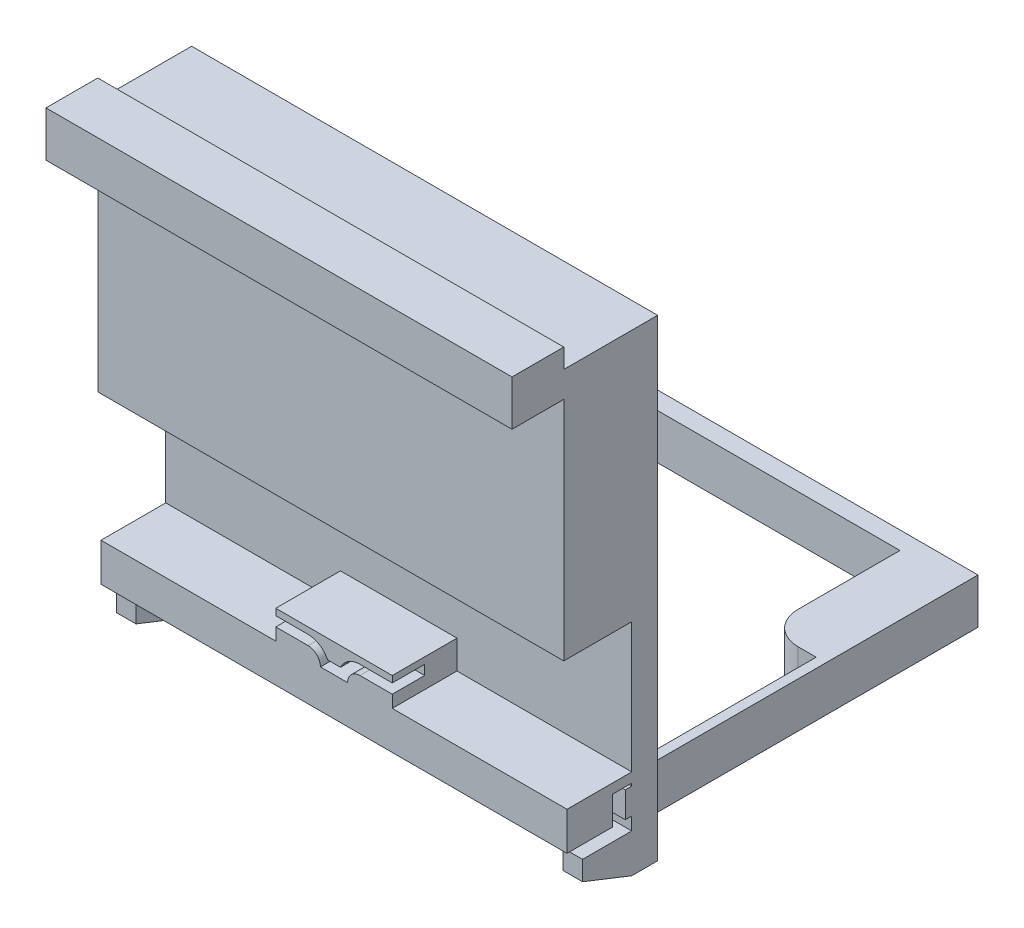
SolidWorks part; units mm, degrees
ref_plane "Alzado" through (0, 0, 0) normal (0, 0, 1) x (1, 0, 0)
ref_plane "Planta" through (0, 0, 0) normal (0, 1, 0) x (1, 0, 0)
ref_plane "Vista lateral" through (0, 0, 0) normal (1, 0, 0) x (0, 0, -1)
sketch "Croquis1" plane through (0, 0, 0) normal (0, 0, 1) x (1, 0, 0)
  line L1 (36, -39.5) -> (-36, -39.5)
  line L5 (36, -39.5) -> (-36, 39.5) construction
  line L6 (36, 39.5) -> (-36, -39.5) construction
  line L7 (-36, -39.5) -> (-33, -39.5)
  line L8 (-36, -39.5) -> (-36, -30.5)
  line L9 (-36, -30.5) -> (-33, -30.5)
  line L10 (-33, -39.5) -> (-33, -30.5)
  line L11 (-36, -30.5) -> (-26.5, -30.5)
  line L12 (-36, -30.5) -> (-36, -27)
  line L13 (-36, -27) -> (-26.5, -27)
  line L14 (-26.5, -30.5) -> (-26.5, -27)
  line L22 (21.8, 10.2) -> (36, 10.2) construction
  line L23 (-36, -27) -> (-36, -23.5) construction
  line L24 (36, -39.5) -> (33, -39.5)
  line L25 (36, -39.5) -> (36, -30.5)
  line L26 (36, -30.5) -> (33, -30.5)
  line L27 (33, -39.5) -> (33, -30.5)
  line L28 (36, -30.5) -> (26.5, -30.5)
  line L29 (36, -30.5) -> (36, -27)
  line L30 (36, -27) -> (26.5, -27)
  line L31 (26.5, -30.5) -> (26.5, -27)
  line L32 (-36, -39.5) -> (-33, -39.5)
  line L33 (-36, -39.5) -> (-36, -32.5)
  line L34 (-36, -32.5) -> (-33, -32.5)
  line L35 (-33, -39.5) -> (-33, -32.5)
  line L36 (36, -39.5) -> (33, -39.5)
  line L37 (36, -39.5) -> (36, -32.5)
  line L38 (36, -32.5) -> (33, -32.5)
  line L39 (33, -39.5) -> (33, -32.5)
  line L40 (36, -22) -> (36, -6) construction
  line L41 (-36, -23.5) -> (36, -23.5)
  line L42 (-36, -23.5) -> (-36, -22)
  line L43 (-36, -22) -> (36, -22)
  line L44 (36, -23.5) -> (36, -22)
  line L45 (-36, -22) -> (36, -22)
  line L49 (-36, -22) -> (-36, 10.2) construction
  line L50 (36, 10.2) -> (36, 17.2) construction
  line L52 (21.8, -6) -> (-21.8, -6)
  line L53 (21.8, -6) -> (21.8, 10.2)
  line L54 (21.8, 10.2) -> (-21.8, 10.2)
  line L55 (-21.8, -6) -> (-21.8, 10.2)
  line L56 (-17.5, 34.5) -> (-36, 34.5)
  line L61 (17.5, 34.5) -> (36, 34.5)
  line L63 (-36, 34.5) -> (36, 34.5)
  line L64 (-36, 34.5) -> (-36, -39.5)
  line L65 (-36, -39.5) -> (36, -39.5)
  line L66 (36, 34.5) -> (36, -39.5)
  line L69 (-17.5, 34.5) -> (17.5, 34.5)
  line L71 (36, 17.2) -> (-36, 17.2)
  line L72 (36, 17.2) -> (36, 34.5)
  line L73 (36, 34.5) -> (-36, 34.5)
  line L74 (-36, 17.2) -> (-36, 34.5)
  point P0 (0, 0)
  point P41 (0, 39.5)
  dimension "D1" = 79
  dimension "D2" = 72
  dimension "D3" = 9
  dimension "D4" = 3
  dimension "D5" = 3.5
  dimension "D6" = 9.5
  dimension "D7" = 9
  dimension "D8" = 3
  dimension "D9" = 3.5
  dimension "D10" = 9.5
  dimension "D11" = 7
  dimension "D12" = 3
  dimension "D13" = 7
  dimension "D14" = 3
  dimension "D15" = 3.5
  dimension "D16" = 1.5
  dimension "D17" = 16
  dimension "D18" = 14.2
  dimension "D19" = 14.2
  dimension "D20" = 16.2
  dimension "D21" = 7
extrude "Saliente-Extruir3" add sketch "Croquis1" along normal blind 4
sketch "Croquis2" plane through (0, 0, 4) normal (0, 0, 1) x (1, 0, 0)
  line L1 (-36, -39.5) -> (-33, -39.5)
  line L2 (-36, -39.5) -> (-36, -33.5)
  line L3 (-36, -33.5) -> (-33, -33.5)
  line L4 (-33, -39.5) -> (-33, -33.5)
  line L5 (36, -39.5) -> (33, -39.5)
  line L6 (36, -39.5) -> (36, -33.5)
  line L7 (36, -33.5) -> (33, -33.5)
  line L8 (33, -39.5) -> (33, -33.5)
  dimension "D1" = 6
  dimension "D2" = 3
  dimension "D3" = 6
  dimension "D4" = 3
extrude "Saliente-Extruir4" add sketch "Croquis2" along normal blind 7.6 contours L2 L1 L4 L3 | L6 L5 L8 L7
sketch "Croquis3" plane through (-36, 0, 0) normal (-1, 0, 0) x (0, 0, 1)
  line L0 (11.6, -33.5) -> (11.6, -36.5) construction
  line L1 (11.6, -39.5) -> (11.6, -33.5) construction
  line L2 (4, -33.5) -> (4, -39.5) construction
  line L3 (11.6, -39.5) -> (0, -39.5) construction
  line L4 (4, -39.5) -> (11.6, -36.5) construction
  line L5 (4, -39.5) -> (11.6, -36.5)
  line L6 (11.6, -36.5) -> (11.6, -39.5)
  line L7 (11.6, -39.5) -> (4, -39.5)
  dimension "D1" = 3
extrude "Cortar-Extruir3" cut sketch "Croquis3" against normal through all contours L7 L5 L6
sketch "Croquis5" plane through (0, 0, 4) normal (0, 0, 1) x (1, 0, 0)
  line L0 (-36, -33.5) -> (-36, -32.5) construction
  line L1 (-36, 34.5) -> (-36, -33.5) construction
  line L2 (36, 34.5) -> (36, -33.5) construction
  line L3 (-36, -32.5) -> (-31, -32.5)
  line L4 (-36, -32.5) -> (-36, -28.5)
  line L5 (-36, -28.5) -> (-31, -28.5)
  line L6 (-31, -32.5) -> (-31, -28.5)
  line L7 (36, -31.5) -> (31, -31.5)
  line L8 (36, -31.5) -> (36, -27.5)
  line L9 (36, -27.5) -> (31, -27.5)
  line L10 (31, -31.5) -> (31, -27.5)
  dimension "D1" = 1
  dimension "D2" = 4
  dimension "D3" = 5
  dimension "D4" = 4
  dimension "D5" = 5
extrude "Saliente-Extruir5" add sketch "Croquis5" along normal blind 1 contours L8 L7 L10 L9 | L4 L3 L6 L5
sketch "Croquis9" plane through (0, 0, 4) normal (0, 0, 1) x (1, 0, 0)
  line L0 (-36, -33.5) -> (-36, -27.1) construction
  line L1 (-36, 34.5) -> (-36, -28.5) construction
  line L2 (36, 34.5) -> (36, -27.5) construction
  line L3 (-36, -27.1) -> (36, -27.1)
  line L4 (-36, -27.1) -> (-36, -25.6)
  line L5 (-36, -25.6) -> (36, -25.6)
  line L6 (36, -27.1) -> (36, -25.6)
  dimension "D1" = 6.4
  dimension "D2" = 1.5
extrude "Saliente-Extruir6" add sketch "Croquis9" along normal blind 8 contours L4 L3 L6 L5
sketch "Croquis10" plane through (0, 0, 12) normal (0, 0, 1) x (1, 0, 0)
  line L1 (-36, -25.6) -> (36, -25.6)
  line L2 (-36, -25.6) -> (-36, -31.5)
  line L3 (-36, -31.5) -> (36, -31.5)
  line L4 (36, -25.6) -> (36, -31.5)
  dimension "D1" = 5.9
extrude "Saliente-Extruir7" add sketch "Croquis10" along normal blind 2
sketch "Croquis11" plane through (0, 0, 14) normal (0, 0, 1) x (1, 0, 0)
  line L1 (-36, -31.5) -> (-26, -31.5)
  line L2 (-36, -31.5) -> (-36, -27.1)
  line L3 (-36, -27.1) -> (-26, -27.1)
  line L4 (-26, -31.5) -> (-26, -27.1)
  line L5 (36, -31.5) -> (26, -31.5)
  line L6 (36, -31.5) -> (36, -27.1)
  line L7 (36, -27.1) -> (26, -27.1)
  line L8 (26, -31.5) -> (26, -27.1)
  dimension "D1" = 4.4
  dimension "D2" = 10
  dimension "D3" = 4.4
  dimension "D4" = 10
extrude "Saliente-Extruir10" add sketch "Croquis11" against normal blind 7
sketch "Croquis14" plane through (0, 0, 4) normal (0, 0, 1) x (1, 0, 0)
  line L0 (-9, -25.6) -> (-9, -23.7)
  line L1 (36, -25.6) -> (-36, -25.6) construction
  line L2 (-9, -21.2) -> (-9, -22.2)
  line L3 (-9, -25.6) -> (9, -25.6)
  line L4 (-9, -25.6) -> (-9, -21.2)
  line L5 (-9, -21.2) -> (9, -21.2)
  line L6 (9, -25.6) -> (9, -21.2)
  line L7 (-9, -23.7) -> (-4, -23.7)
  line L8 (-9, -22.2) -> (-4, -22.2)
  line L9 (-9, -23.7) -> (-2.1, -23.7)
  line L10 (9, -22.2) -> (4, -22.2)
  line L11 (9, -23.7) -> (4, -23.7)
  line L12 (-2.1, -25.6) -> (2.1, -25.6)
  line L13 (9, -23.7) -> (9, -22.2)
  line L14 (-9, -23.7) -> (-9, -22.2)
  line L15 (0, -25.6) -> (0, -24.1)
  line L16 (1, -24.1) -> (-1, -24.1)
  arc A0 (-4, -23.7) -> (-2.1, -25.6) centre (-4, -25.6) cw
  arc A1 (-4, -22.2) -> (-1, -24.1) centre (-4, -25.5184) cw
  arc A2 (4, -23.7) -> (2.1, -25.6) centre (4, -25.6) ccw
  arc A3 (4, -22.2) -> (1, -24.1) centre (4, -25.5184) ccw
  point P25 (0, -24.1)
  dimension "D7" = 5
  dimension "D9" = 1.5
  dimension "D10" = 1
  dimension "D1" = 1.9
  dimension "D2" = 4.4
  dimension "D3" = 18
  dimension "D4" = 1
  dimension "D5" = 5
  dimension "D6" = 5
  dimension "D8" = 5
extrude "Saliente-Extruir14" add sketch "Croquis14" along normal up to surface (10 mm away) up to face at (0, -28.55, 14)
sketch "Croquis15" plane through (0, 0, 4) normal (0, 0, 1) x (1, 0, 0)
  line L1 (-9, -21.2) -> (9, -21.2)
  line L2 (-9, -21.2) -> (-9, -25.6)
  line L3 (-9, -25.6) -> (9, -25.6)
  line L4 (9, -21.2) -> (9, -25.6)
extrude "Saliente-Extruir15" add sketch "Croquis15" along normal blind 5
sketch "Croquis16" plane through (0, 0, 4) normal (0, 0, 1) x (1, 0, 0)
  line L1 (-36, 34.5) -> (36, 34.5)
  line L2 (-36, 34.5) -> (-36, -5.5)
  line L3 (-36, -5.5) -> (36, -5.5)
  line L4 (36, 34.5) -> (36, -5.5)
  line L5 (36, 34.5) -> (36, -25.6) construction
  dimension "D1" = 40
  dimension "D2" = 72
extrude "Saliente-Extruir16" add sketch "Croquis16" along normal blind 10.5
sketch "Croquis17" plane through (0, 0, 14.5) normal (0, 0, 1) x (1, 0, 0)
  line L1 (-36, 34.5) -> (36, 34.5)
  line L2 (-36, 34.5) -> (-36, 29.5)
  line L3 (-36, 29.5) -> (36, 29.5)
  line L4 (36, 34.5) -> (36, 29.5)
  line L5 (36, -5.5) -> (36, 34.5) construction
  dimension "D1" = 5
  dimension "D2" = 72
extrude "Saliente-Extruir17" add sketch "Croquis17" along normal blind 8 contours L2 L1 L4 L3
sketch "Croquis18" plane through (0, 34.5, 0) normal (0, 1, 0) x (1, 0, 0)
  line L1 (-36, -22.5) -> (36, -22.5)
  line L2 (-36, -22.5) -> (-36, -14.5)
  line L3 (-36, -14.5) -> (36, -14.5)
  line L4 (36, -22.5) -> (36, -14.5)
  line L5 (36, -22.5) -> (36, 0) construction
  dimension "D1" = 8
  dimension "D2" = 72
extrude "Saliente-Extruir19" add sketch "Croquis18" along normal blind 2
sketch "Croquis19" plane through (0, 0, 0) normal (0, 0, -1) x (-1, 0, 0)
  line L1 (-36, 34.5) -> (36, 34.5)
  line L2 (-36, 34.5) -> (-36, 33.5)
  line L3 (-36, 33.5) -> (36, 33.5)
  line L4 (36, 34.5) -> (36, 33.5)
  dimension "D1" = 1
  dimension "D2" = 72
extrude "Cortar-Extruir4" cut sketch "Croquis19" against normal blind 14.5
sketch "Croquis20" plane through (0, 0, 0) normal (0, 0, -1) x (-1, 0, 0)
  line L0 (-36, -39.5) -> (-29.5, -39.5) construction
  line L5 (-36, -39.5) -> (36, -39.5) construction
  line L7 (-29.5, -39.5) -> (29.5, -39.5)
  line L8 (-29.5, -39.5) -> (-29.5, -32.5)
  line L9 (-29.5, -32.5) -> (29.5, -32.5)
  line L10 (29.5, -39.5) -> (29.5, -32.5)
  dimension "D1" = 6.5
  dimension "D2" = 7
  dimension "D3" = 59
extrude "Saliente-Extruir20" add sketch "Croquis20" along normal blind 65
sketch "Croquis26" plane through (0, -32.5, 0) normal (0, 1, 0) x (1, 0, 0)
  line L0 (0, 25.5) -> (0, 5) construction
  line L1 (-29.5, 65) -> (-24.5, 65) construction
  line L2 (-29.5, 65) -> (29.5, 65) construction
  line L3 (-24.5, 65) -> (-24.5, 43.25) construction
  line L4 (-24.5, 43.25) -> (-24.5, 53.25) construction
  line L5 (18, 5) -> (-18, 5)
  line L6 (-18, 5) -> (-23, 5) construction
  line L7 (18, 5) -> (23, 5) construction
  line L8 (-24.5, 53.25) -> (-22, 53.25) construction
  line L9 (-22, 53.25) -> (-22, 33.25) construction
  line L10 (-22, 33.25) -> (-12, 33.25) construction
  line L11 (-22, 53.25) -> (-22, 33.25)
  line L12 (-22, 33.25) -> (-12, 33.25)
  line L13 (-12, 33.25) -> (-12, 7.5)
  line L14 (-12, 7.5) -> (28, 7.5)
  line L15 (28, 7.5) -> (28, 32.5)
  line L16 (28, 32.5) -> (20.1928, 32.5)
  line L17 (20.1928, 32.5) -> (20.1928, 53.25)
  line L18 (20.1928, 53.25) -> (-22, 53.25)
  circle A4 centre (-18, 5) radius 1.25
  circle A5 centre (18, 5) radius 1.25
  circle A6 centre (23, 5) radius 1.3
  circle A7 centre (-23, 5) radius 1.3
  circle A8 centre (-24.5, 43.25) radius 1.25
  point P14 (0, 5)
  dimension "D4" = 2.5
  dimension "D6" = 2.5
  dimension "D7" = 20
  dimension "D9" = 18
  dimension "D10" = 2.5
  dimension "D11" = 2.5
  dimension "D14" = 2.6
  dimension "D15" = 2.6
  dimension "D5" = 10
  dimension "D16" = 25.75
  dimension "D1" = 20.5
  dimension "D2" = 5
  dimension "D3" = 21.75
  dimension "D8" = 10
  dimension "D12" = 5
  dimension "D13" = 5
  dimension "D17" = 40
extrude "Cortar-Extruir5" cut sketch "Croquis26" against normal blind 10
fillet "Redondeo1" radius 5 2 edges at (20.1928, -36, -32.5) (-12, -36, -33.25)
sketch "Croquis27" plane through (0, -32.5, 0) normal (0, 1, 0) x (1, 0, 0)
  line L0 (29.5, 65) -> (29.5, 0) construction
  line L1 (-29.5, 65) -> (29.5, 65)
  line L2 (-29.5, 65) -> (-29.5, 56)
  line L3 (-29.5, 56) -> (29.5, 56)
  line L4 (29.5, 65) -> (29.5, 56)
  dimension "D1" = 9
extrude "Cortar-Extruir6" cut sketch "Croquis27" against normal up to next
